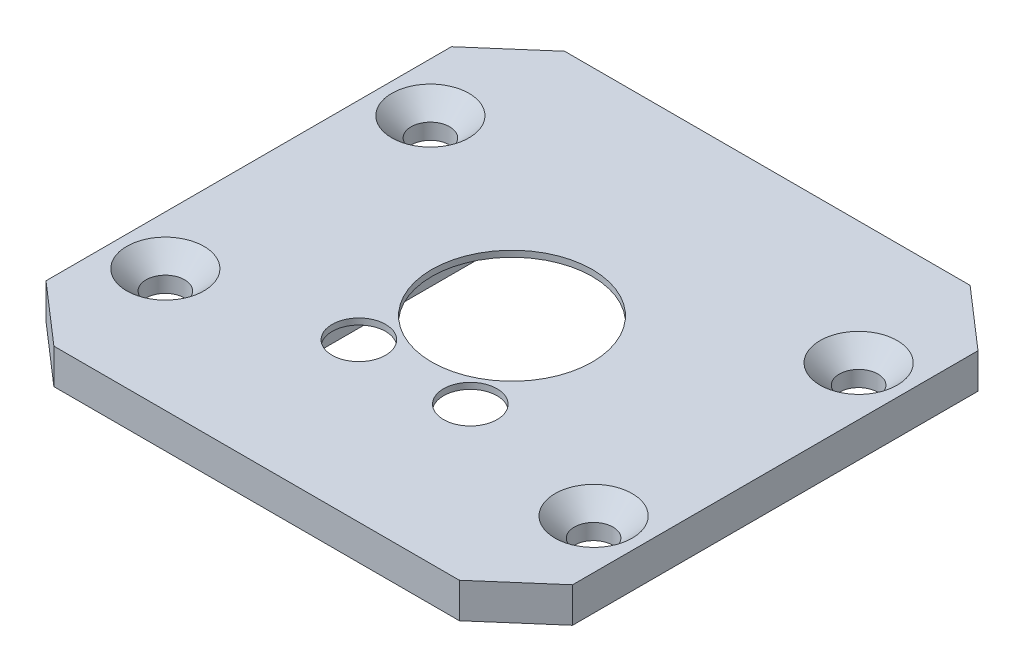
SolidWorks part; units mm, degrees
ref_plane "Front Plane" through (0, 0, 0) normal (0, 0, 1) x (1, 0, 0)
ref_plane "Top Plane" through (0, 0, 0) normal (0, 1, 0) x (1, 0, 0)
ref_plane "Right Plane" through (0, 0, 0) normal (1, 0, 0) x (0, 0, -1)
sketch "Sketch1" plane through (0, 0, 0) normal (0, 1, 0) x (1, 0, 0)
  line L8 (-10.1473, 19.7976) -> (-10.1473, -3.3024)
  line L9 (-10.1473, -3.3024) -> (-6.6973, -6.3024)
  line L10 (-6.6973, -6.3024) -> (16.4027, -6.3024)
  line L11 (16.4027, -6.3024) -> (19.8527, -3.3024)
  line L12 (19.8527, -3.3024) -> (19.8527, 19.7976)
  line L13 (19.8527, 19.7976) -> (16.4027, 22.7976)
  line L14 (16.4027, 22.7976) -> (-6.6973, 22.7976)
  line L15 (-6.6973, 22.7976) -> (-10.1473, 19.7976)
extrude "Boss-Extrude1" add sketch "Sketch1" along normal blind 2
sketch "Sketch3" plane through (0, 2, 0) normal (0, 1, 0) x (1, 0, 0)
  circle A0 centre (-7.3473, 15.7976) radius 0.5
  circle A1 centre (17.0527, 15.7976) radius 0.5
  circle A2 centre (17.0527, 0.6976) radius 0.5
  circle A3 centre (-7.3473, 0.6976) radius 0.5
  point P0 (-7.3473, 15.7976)
  point P3 (17.0527, 15.7976)
  point P6 (17.0527, 0.6976)
  point P9 (-7.3473, 0.6976)
  dimension "D1" = 1
  dimension "D2" = 1
  dimension "D3" = 1
  dimension "D4" = 1
hole_wizard "CSK for M2 Flat Head Machine Screw1" positions "Sketch3" profile "Sketch4" countersink size "M2" standard "ANSI Metric"
sketch "Sketch4" plane through (-7.3473, 2, -15.7976) normal (1, 0, 0) x (0, 0, 1)
  line L0 (0, 0) -> (0, 4.6609)
  line L1 (0, 4.6609) -> (1.1, 4)
  line L2 (1.1, 4) -> (1.1, 1.1)
  line L3 (1.1, 1.1) -> (2.2, 0)
  line L5 (2.2, 0) -> (0, 0)
  line L6 (-1.1, 1.1) -> (-2.2, 0) construction
  line L10 (0, 4.6609) -> (-1.1, 4) construction
  line L11 (0, -6.35) -> (0, 107.95) construction
  dimension "Hole Dia." = 2.2
  dimension "Hole Depth" = 4
  dimension "Near C'Sink Dia." = 4.4
  dimension "Near C'Sink Angle" = 90
  dimension "Drill Angle" = 118
sketch "Sketch9" plane through (0, 0, 0) normal (0, 1, 0) x (1, 0, 0)
  line L0 (-10.1473, 19.7976) -> (-10.1473, -3.3024) construction
  line L1 (10.6027, 16.7976) -> (-0.8973, 16.7976)
  line L2 (10.6027, 16.7976) -> (10.6027, -0.3024)
  line L3 (10.6027, -0.3024) -> (-0.8973, -0.3024)
  line L4 (-0.8973, 16.7976) -> (-0.8973, -0.3024)
  line L5 (10.6027, 16.7976) -> (-0.8973, -0.3024) construction
  line L6 (10.6027, -0.3024) -> (-0.8973, 16.7976) construction
  line L7 (16.4027, 22.7976) -> (-6.6973, 22.7976) construction
  point P0 (4.8527, 8.2476)
  point P7 (-10.1473, 8.2476)
  point P10 (4.8527, 22.7976)
  dimension "D1" = 11.5
  dimension "D2" = 17.1
extrude "Cut-Extrude1" cut sketch "Sketch9" along normal blind 1.651
sketch "Sketch11" plane through (0, 1.651, 0) normal (0, -1, 0) x (1, 0, 0)
  line L0 (-0.8973, 0.3024) -> (10.6027, 0.3024) construction
  line L1 (10.6027, 0.3024) -> (10.6027, -16.7976) construction
  line L2 (1.6777, -2.6976) -> (8.0277, -2.6976) construction
  circle A0 centre (4.8527, -8.2476) radius 4.572
  circle A1 centre (8.0277, -2.6976) radius 1.524
  circle A2 centre (1.6777, -2.6976) radius 1.524
  point P0 (4.8527, 0.3024)
  point P1 (10.6027, -8.2476)
  point P12 (4.8527, -2.6976)
  point P13 (0, 0)
  dimension "D1" = 9.144
  dimension "D2" = 3.048
  dimension "D3" = 3.048
  dimension "D5" = 3
  dimension "D4" = 6.35
extrude "Cut-Extrude2" cut sketch "Sketch11" against normal through all
